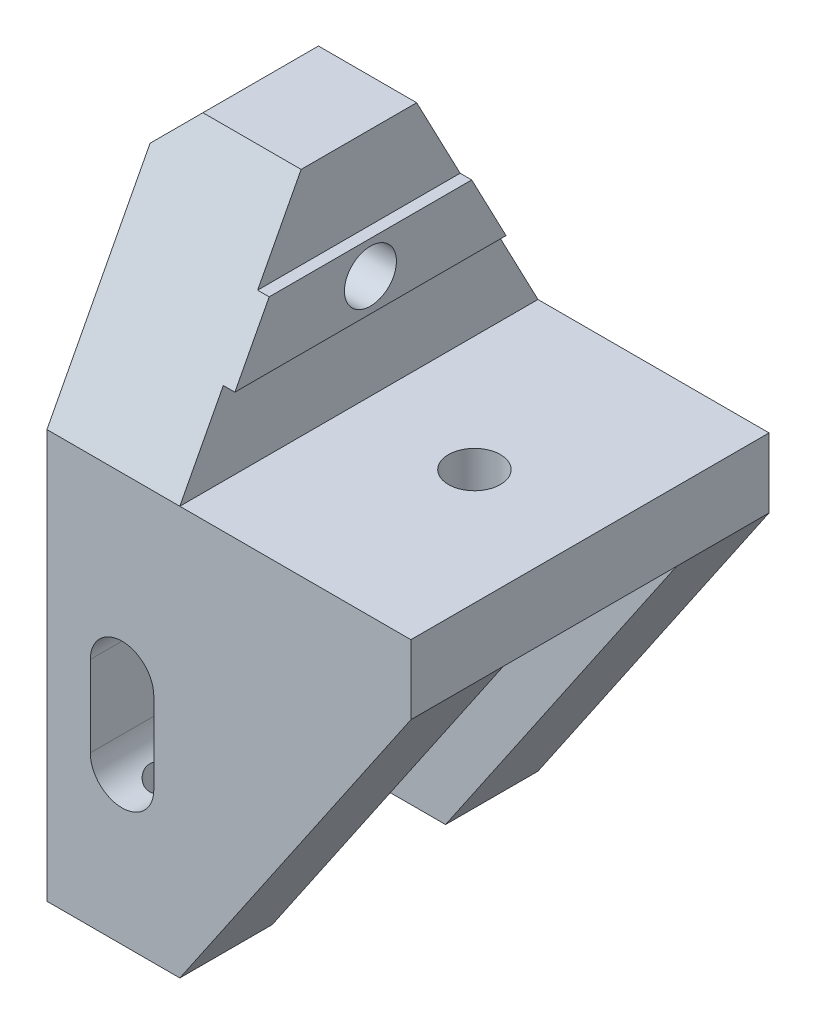
SolidWorks part; units mm, degrees
ref_plane "Plano frontal" through (0, 0, 0) normal (0, 0, 1) x (1, 0, 0)
ref_plane "Plano superior" through (0, 0, 0) normal (0, 1, 0) x (1, 0, 0)
ref_plane "Plano direito" through (0, 0, 0) normal (1, 0, 0) x (0, 0, -1)
sketch "Esboço1" plane through (0, 0, 0) normal (0, 0, 1) x (1, 0, 0)
  line L0 (-28.5, 20) -> (-31.5, 17)
  line L1 (-31.5, 17) -> (-31.5, -2.3605)
  line L2 (-31.5, -2.3605) -> (-20, -9)
  line L4 (0, -6) -> (0, 0)
  line L5 (-20, 0) -> (-20, -9) construction
  line L6 (0, 0) -> (-20, 0)
  line L7 (-20, 0) -> (-20, 7.17)
  line L8 (-20, 7.17) -> (-19, 7.17)
  line L9 (-19, 7.17) -> (-19, 12.83)
  line L10 (-19, 12.83) -> (-20, 12.83)
  line L11 (-20, 12.83) -> (-20, 20)
  line L12 (-20, 20) -> (-28.5, 20)
  line L13 (-3, -9) -> (0, -6)
  line L14 (-20, -9) -> (-3, -9)
  point P8 (0, -9)
  dimension "D1" = 31.5
  dimension "D2" = 60
  dimension "D5" = 11.5
  dimension "D6" = 20
  dimension "D8" = 9
  dimension "D10" = 135
  dimension "D11" = 1
  dimension "D12" = 7.17
  dimension "D13" = 7.17
  dimension "D16" = 3
extrude "Ressalto-extrusão1" add sketch "Esboço1" along normal blind 15
sketch "Esboço2" plane through (-31.5, 0, 0) normal (-1, 0, 0) x (0, 0, 1)
  line L0 (7.5, 20) -> (7.5, -9) construction
  line L1 (15, 20) -> (0, 20) construction
  line L3 (15, -9) -> (0, -9) construction
  circle A0 centre (7.5, 10) radius 2.25
  dimension "D1" = 4.5
  dimension "D2" = 10
extrude "Corte-extrusão1" cut sketch "Esboço2" against normal through all contours A0
sketch "Esboço3" plane through (0, -9, 0) normal (0, -1, 0) x (1, 0, 0)
  line L0 (-10, 15) -> (-10, 0) construction
  line L3 (0, 7.5) -> (-31.5, 7.5) construction
  line L4 (0, 15) -> (0, 0) construction
  line L6 (-31.5, 15) -> (-31.5, 0) construction
  line L7 (-20, 15) -> (-20, 0) construction
  circle A0 centre (-10, 7.5) radius 2.25
  dimension "D1" = 4.5
  dimension "D2" = 10
extrude "Corte-extrusão2" cut sketch "Esboço3" against normal through all both and the other way through all
ref_plane "Plano1" through (0, 0, 7.5) normal (0, 0, 1) x (1, 0, 0)
sketch "Esboço4" plane through (0, 0, 15) normal (0, 0, 1) x (1, 0, 0)
  line L13 (-31.5, -2.3605) -> (-31.5, -35.3605)
  line L14 (-31.5, -35.3605) -> (-20, -35.3605)
  line L16 (-25, -5.6802) -> (-25, -10.451) construction
  line L19 (0, 0) -> (0, -6)
  line L20 (-25, -22.3605) -> (-25, -15.3605) construction
  line L21 (-27.75, -22.3605) -> (-27.75, -15.3605)
  line L22 (-22.25, -22.3605) -> (-22.25, -15.3605)
  line L23 (-20, -35.3605) -> (0, -6)
  line L25 (-20, 0) -> (-20, -35.3605) construction
  line L39 (-20, 20) -> (-28.5, 20)
  line L40 (-28.5, 20) -> (-31.5, 17)
  line L41 (-31.5, 17) -> (-31.5, -2.3605)
  line L42 (-31.5, -2.3605) -> (-20, -9)
  line L43 (-31.5, -2.3605) -> (-20, -9)
  line L46 (-20, -9) -> (-3, -9)
  line L47 (-3, -9) -> (0, -6)
  line L48 (0, -6) -> (0, 0)
  line L49 (0, 0) -> (-20, 0)
  line L50 (-20, 0) -> (-20, 7.17)
  line L51 (-20, 7.17) -> (-19, 7.17)
  line L52 (-19, 7.17) -> (-19, 12.83)
  line L53 (-19, 12.83) -> (-20, 12.83)
  line L54 (-20, 12.83) -> (-20, 20)
  line L55 (-20, 20) -> (-28.5, 20)
  line L56 (-28.5, 20) -> (-31.5, 17)
  line L57 (-31.5, 17) -> (-31.5, -2.3605)
  line L64 (0, -6) -> (0, 0)
  line L65 (0, 0) -> (-20, 0)
  line L66 (-20, 0) -> (-20, 7.17)
  line L67 (-20, 7.17) -> (-19, 7.17)
  line L68 (-19, 7.17) -> (-19, 12.83)
  line L69 (-19, 12.83) -> (-20, 12.83)
  line L70 (-20, 12.83) -> (-20, 20)
  arc A0 (-27.75, -22.3605) -> (-22.25, -22.3605) centre (-25, -22.3605) ccw
  arc A1 (-22.25, -15.3605) -> (-27.75, -15.3605) centre (-25, -15.3605) ccw
  circle A2 centre (-25, -15.3605) radius 10 construction
  point P22 (-25, -18.8605)
  dimension "D4" = 2.75
  dimension "D6" = 20
  dimension "D1" = 33
  dimension "D3" = 7
  dimension "D5" = 13
  dimension "D7" = 6.5
  dimension "D2" = 0
extrude "Ressalto-extrusão2" add sketch "Esboço4" along normal blind 8
mirror "Espelhar1" about plane through (0, 0, 7.5) normal (0, 0, 1) of "Ressalto-extrusão2"
sketch "Esboço5" plane through (0, 0, -8) normal (0, 0, -1) x (-1, 0, 0)
  line L1 (25, -10.6608) -> (20.93, -13.0107)
  line L2 (20.93, -13.0107) -> (20.93, -17.9)
  line L3 (22.9222, -18.8605) -> (22.965, -18.8852)
  line L4 (27.035, -18.8852) -> (27.0778, -18.8605)
  line L5 (29.07, -17.9) -> (29.07, -13.0107)
  line L6 (29.07, -13.0107) -> (25, -10.6608)
  line L7 (25, -27.0601) -> (29.07, -24.7103)
  line L8 (29.07, -24.7103) -> (29.07, -17.9)
  line L9 (27.0778, -18.8605) -> (27.035, -18.8357)
  line L10 (22.965, -18.8357) -> (22.9222, -18.8605)
  line L11 (20.93, -17.9) -> (20.93, -24.7103)
  line L12 (20.93, -24.7103) -> (25, -27.0601)
  circle A0 centre (25, -15.3605) radius 4.07 construction
  circle A1 centre (25, -22.3605) radius 4.07 construction
  arc M25 (22.25, -15.3605) -> (27.75, -15.3605) centre (25, -15.3605) cw
  line M26 (27.75, -15.3605) -> (27.75, -22.3605)
  arc M27 (27.75, -22.3605) -> (22.25, -22.3605) centre (25, -22.3605) cw
  line M28 (22.25, -22.3605) -> (22.25, -15.3605)
  dimension "D1" = 8.14
extrude "Corte-extrusão3" cut sketch "Esboço5" against normal blind 4 contours L11 L12 L7 L8 L5 L6 L1 L2 M28 M25 M26 M27
sketch "Esboço6" plane through (0, -35.3605, 0) normal (0, -1, 0) x (1, 0, 0)
  line L0 (-31.5, 23) -> (-31.5, 15) construction
  line L1 (-25, 19) -> (-25, -4) construction
  line L2 (-25, 19) -> (-31.5, 19) construction
  line L3 (-25, -4) -> (-31.5, -4) construction
  line L4 (-31.5, -8) -> (-31.5, 0) construction
  circle A0 centre (-25, 19) radius 1.6
  circle A1 centre (-25, -4) radius 1.6
  dimension "D2" = 3.2
  dimension "D1" = 6.5
extrude "Corte-extrusão4" cut sketch "Esboço6" against normal up to surface (10.25 mm away)
ref_plane "Plano2" through (0, -32.3605, 0) normal (0, -1, 0) x (-1, 0, 0)
sketch "Esboço7" plane through (0, -32.3605, 0) normal (0, -1, 0) x (-1, 0, 0)
  line L0 (26.6743, -21.9) -> (33, -21.9)
  line L1 (26.6743, 1.1) -> (28.3486, 4) construction
  line L2 (28.3486, 4) -> (26.6743, 6.9) construction
  line L3 (26.6743, 6.9) -> (23.3257, 6.9)
  line L4 (23.3257, 6.9) -> (21.6514, 4)
  line L5 (21.6514, 4) -> (23.3257, 1.1)
  line L6 (23.3257, 1.1) -> (26.6743, 1.1)
  line L7 (28.3486, -19) -> (26.6743, -16.1) construction
  line L8 (26.6743, -16.1) -> (23.3257, -16.1)
  line L9 (23.3257, -16.1) -> (21.6514, -19)
  line L10 (21.6514, -19) -> (23.3257, -21.9)
  line L11 (23.3257, -21.9) -> (26.6743, -21.9)
  line L12 (26.6743, -21.9) -> (28.3486, -19) construction
  line L13 (33, -21.9) -> (33, -16.1)
  line L14 (33, -16.1) -> (26.6743, -16.1)
  line L15 (26.6743, 1.1) -> (33, 1.1)
  line L16 (33, 1.1) -> (33, 6.9)
  line L17 (33, 6.9) -> (26.6743, 6.9)
  line L18 (31.5, 8) -> (31.5, 0) construction
  circle A0 centre (25, 4) radius 2.9 construction
  circle A1 centre (25, -19) radius 2.9 construction
  dimension "D1" = 5.8
  dimension "D2" = 1.5
extrude "Corte-extrusão5" cut sketch "Esboço7" against normal blind 3
sketch "Esboço8" plane through (0, 0, 0) normal (0, 0, 1) x (1, 0, 0)
  circle A0 centre (-25, -15.3605) radius 12.5
  dimension "D1" = 25
extrude "Corte-extrusão6" cut sketch "Esboço8" along normal up to surface (15 mm away) up to face at (-25, -18.8605, 15)
sketch "Esboço9" plane through (-31.5, 0, 0) normal (-1, 0, 0) x (0, 0, 1)
  line L0 (-8, 0) -> (2.5, 20)
  line L1 (-8, 17) -> (-8, -35.3605) construction
  line L2 (23, 20) -> (-8, 20) construction
  line L3 (2.5, 20) -> (12.5, 20)
  line L4 (12.5, 20) -> (23, 0)
  line L5 (23, 17) -> (23, -35.3605) construction
  line L6 (23, 0) -> (-8, 0) construction
  line L7 (23, 0) -> (-8, 0) construction
  line L8 (7.5, 20) -> (7.5, 10) construction
  line L9 (-8, 0) -> (-8, 29.4588)
  line L10 (-8, 29.4588) -> (23, 29.4588)
  line L11 (23, 29.4588) -> (23, 0)
  dimension "D1" = 10
extrude "Corte-extrusão7" cut sketch "Esboço9" against normal through all both and the other way through all
sketch "Esboço10" plane through (-31.5, 0, 0) normal (-1, 0, 0) x (0, 0, 1)
  circle A0 centre (7.5, 10) radius 5
  dimension "D1" = 10
extrude "Corte-extrusão8" cut sketch "Esboço10" against normal blind 6
sketch "Esboço11" plane through (0, -9, 0) normal (0, -1, 0) x (1, 0, 0)
  circle A0 centre (-10, 7.5) radius 5
  dimension "D1" = 10
extrude "Corte-extrusão9" cut sketch "Esboço11" against normal blind 4
